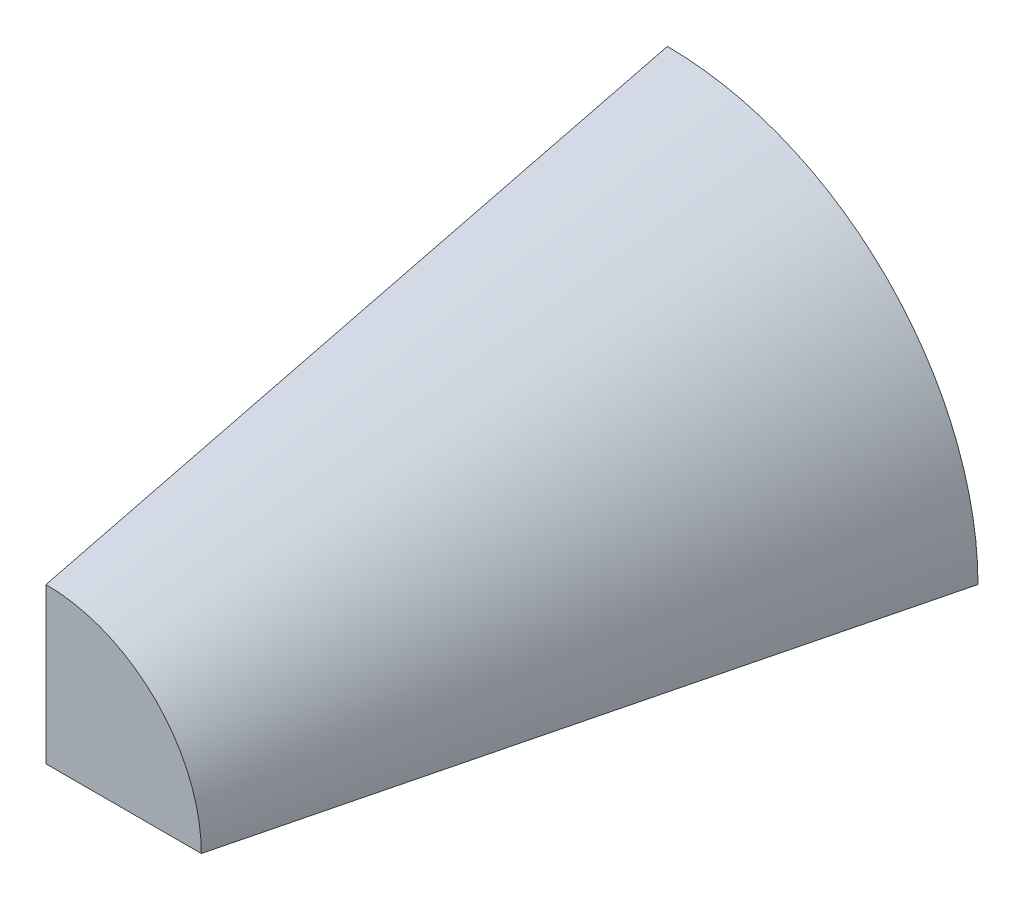
SolidWorks part; units mm, degrees
ref_plane "Front Plane" through (0, 0, 0) normal (0, 0, 1) x (1, 0, 0)
ref_plane "Top Plane" through (0, 0, 0) normal (0, 1, 0) x (1, 0, 0)
ref_plane "Right Plane" through (0, 0, 0) normal (1, 0, 0) x (0, 0, -1)
ref_plane "plane:profile-xz" through (0, 0, 0) normal (0, -1, 0) x (1, 0, 0)
sketch "sketch:main-profile" plane through (0, 0, 0) normal (0, -1, 0) x (1, 0, 0)
  line L0 (0, 0) -> (10, 0)
  line L1 (10, 0) -> (5, 20)
  line L2 (5, 20) -> (0, 20)
  line L3 (0, 20) -> (0, 0)
  line L4 (0, -5) -> (0, 25) construction
revolve "feature:frustum" add sketch "sketch:main-profile" angle 90 about L4
